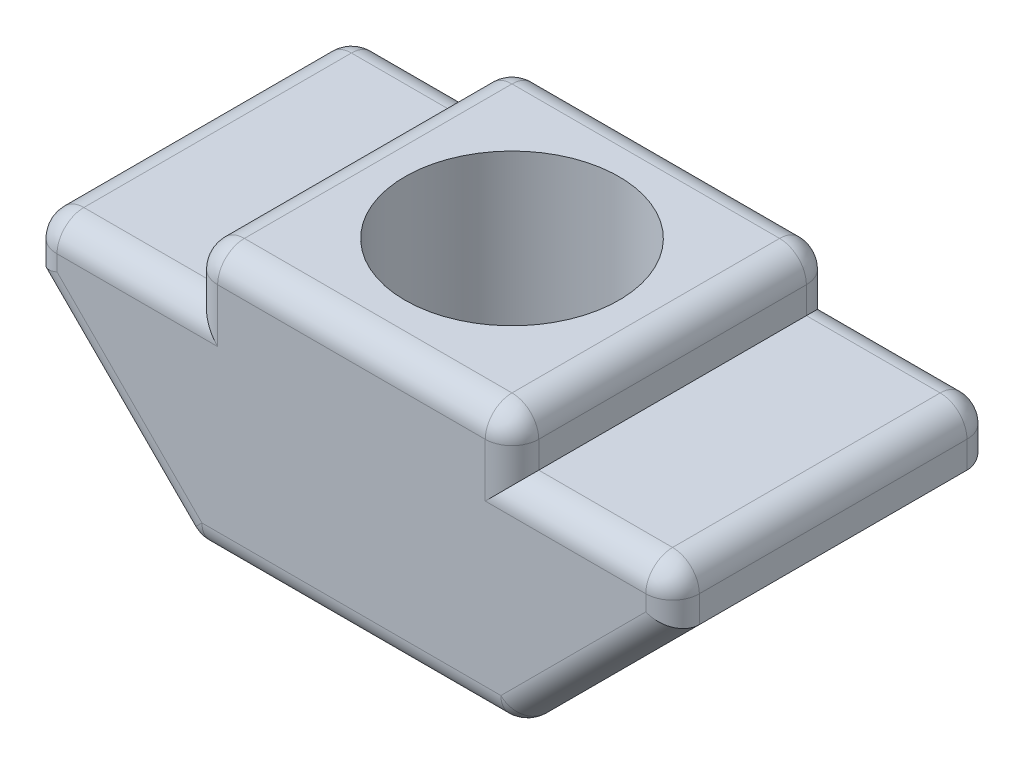
SolidWorks part; units mm, degrees
ref_plane "Front Plane" through (0, 0, 0) normal (0, 0, 1) x (1, 0, 0)
ref_plane "Top Plane" through (0, 0, 0) normal (0, 1, 0) x (1, 0, 0)
ref_plane "Right Plane" through (0, 0, 0) normal (1, 0, 0) x (0, 0, -1)
sketch "Sketch1" plane through (0, 0, 0) normal (0, 0, 1) x (1, 0, 0)
  line L0 (0, 0) -> (6, 0)
  line L1 (6, 0) -> (9, 3)
  line L2 (9, 3) -> (9, 4)
  line L3 (9, 4) -> (6, 4)
  line L4 (6, 4) -> (6, 5)
  line L5 (6, 5) -> (0, 5)
  line L6 (0, 5) -> (0, 4)
  line L7 (0, 4) -> (-3, 4)
  line L8 (-3, 4) -> (-3, 3)
  line L9 (-3, 3) -> (0, 0)
  dimension "D1" = 6
  dimension "D2" = 6
  dimension "D3" = 1
  dimension "D4" = 1
  dimension "D5" = 1
  dimension "D6" = 1
  dimension "D7" = 135
  dimension "D8" = 135
  dimension "D9" = 12
extrude "Boss-Extrude1" add sketch "Sketch1" along normal blind 6
fillet "Fillet1" radius 0.5 26 edges at (3, 0, 0) (7.5, 1.5, 0) (9, 3.5, 0) (7.5, 4, 0) (6, 4.5, 0) (3, 5, 0) (0, 4.5, 0) (-1.5, 4, 0) (-3, 3.5, 0) (-1.5, 1.5, 0) (-1.5, 1.5, 6) (0, 0, 3) (3, 0, 6) (6, 0, 3) (7.5, 1.5, 6) (9, 3.5, 6) (-3, 3.5, 6) (-1.5, 4, 6) (7.5, 4, 6) (9, 4, 3) (6, 4.5, 6) (0, 4.5, 6) (-3, 4, 3) (0, 5, 3) (6, 5, 3) (3, 5, 6)
sketch "Sketch2" plane through (0, 5, 0) normal (0, 1, 0) x (1, 0, 0)
  line L0 (5.5, -3) -> (0.5, -3) construction
  line L1 (5.5, -5.5) -> (5.5, -0.5) construction
  line L2 (0.5, -0.5) -> (0.5, -5.5) construction
  line L3 (3, -0.5) -> (3, -5.5) construction
  line L4 (5.5, -0.5) -> (0.5, -0.5) construction
  line L5 (0.5, -5.5) -> (5.5, -5.5) construction
  circle A0 centre (3, -3) radius 2
  dimension "D1" = 4
extrude "Cut-Extrude1" cut sketch "Sketch2" against normal through all
